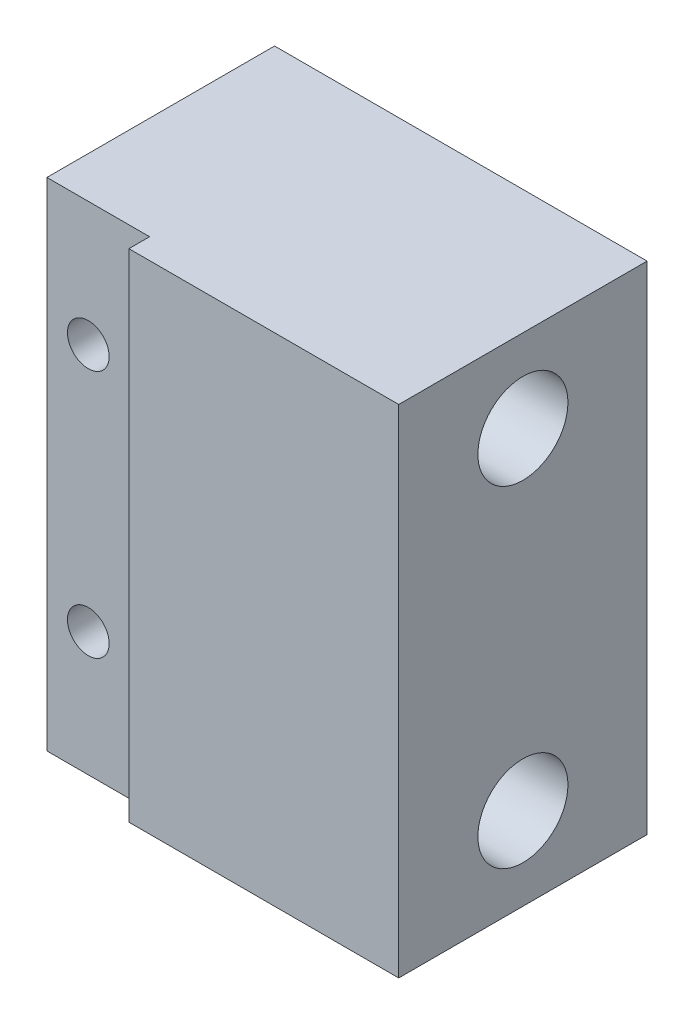
SolidWorks part; units mm, degrees
material "Delrin 2700 NC010, Low Viscosity Acetal Copolymer (SS)"
ref_plane "Front Plane" through (0, 0, 0) normal (0, 0, 1) x (1, 0, 0)
ref_plane "Top Plane" through (0, 0, 0) normal (0, 1, 0) x (1, 0, 0)
ref_plane "Right Plane" through (0, 0, 0) normal (1, 0, 0) x (0, 0, -1)
sketch "Sketch1" plane through (0, 0, 0) normal (1, 0, 0) x (0, 0, -1)
  line L1 (-4.7625, -9.525) -> (4.7625, -9.525)
  line L2 (-4.7625, -9.525) -> (-4.7625, 9.525)
  line L3 (-4.7625, 9.525) -> (4.7625, 9.525)
  line L4 (4.7625, -9.525) -> (4.7625, 9.525)
  line L5 (-4.7625, -9.525) -> (4.7625, 9.525) construction
  line L6 (-4.7625, 9.525) -> (4.7625, -9.525) construction
  point P0 (0, 0)
  dimension "D1" = 9.525
  dimension "D2" = 19.05
extrude "Boss-Extrude1" add sketch "Sketch1" against normal blind 14.2875
hole_wizard "#8-32 Tapped Hole1" positions "Sketch2" profile "Sketch3" tap size "#8-32" standard "ANSI Inch"
sketch "Sketch2" plane through (0, 0, 0) normal (1, 0, 0) x (0, 0, -1)
  point P0 (0, 6.35)
  point P2 (0, -6.35)
  point P13 (0, 0)
  dimension "D1" = 12.7
  dimension "D2" = 6.35
cosmetic thread "Hole Thread1" parameters "D1"=8.3312, "D2"=4.1656
cosmetic thread "Hole Thread2" parameters "D1"=8.3312, "D2"=4.1656
sketch "Sketch3" plane through (0, 6.35, 0) normal (0, 1, 0) x (0, 0, -1)
  line L0 (0, 0) -> (0, 12.4678)
  line L1 (0, 12.4678) -> (1.7272, 11.43)
  line L2 (1.7272, 11.43) -> (1.7272, 0)
  line L5 (1.7272, 0) -> (0, 0)
  line L10 (0, 12.4678) -> (-1.7272, 11.43) construction
  line L11 (0, -6.35) -> (0, 107.95) construction
  dimension "Tap Drill Dia." = 3.4544
  dimension "Tap Drill Depth" = 11.43
  dimension "Drill Angle" = 118
sketch "Sketch4" plane through (0, 9.525, 0) normal (0, 1, 0) x (1, 0, 0)
  line L0 (0, 4.7625) -> (0, -4.7625) construction
  line L1 (-14.2875, -4.7625) -> (-10.35, -4.7625)
  line L2 (-14.2875, -4.7625) -> (-14.2875, -3.9688)
  line L3 (-14.2875, -3.9688) -> (-10.35, -3.9688)
  line L4 (-10.35, -4.7625) -> (-10.35, -3.9688)
  dimension "D1" = 10.35
  dimension "D2" = 0.7937
extrude "Cut-Extrude1" cut sketch "Sketch4" against normal through all
hole_wizard "M2x0.4 Tapped Hole1" positions "Sketch5" profile "Sketch6" tap size "M2x0.4" standard "ANSI Metric" end condition through all
sketch "Sketch5" plane through (0, 0, 3.9687) normal (0, 0, 1) x (1, 0, 0)
  line L0 (-12.7, 4.765) -> (-12.7, -4.765) construction
  line L2 (0, 9.525) -> (0, -9.525) construction
  point P0 (-12.7, -4.765)
  point P2 (-12.7, 4.765)
  point P10 (-12.7, 0)
  dimension "D1" = 9.53
  dimension "D2" = 12.7
sketch "Sketch6" plane through (-12.7, -4.765, 3.9687) normal (1, 0, 0) x (0, -1, 0)
  line L0 (0, 0) -> (0, 8.7312)
  line L1 (0, 8.7312) -> (0.8, 8.7312)
  line L2 (0.8, 8.7312) -> (0.8, 0)
  line L5 (0.8, 0) -> (0, 0)
  line L11 (0, -6.35) -> (0, 107.95) construction
  dimension "Thru Tap Drill Dia." = 1.6
  dimension "Thru Tap Drill Depth" = 8.7312
cosmetic thread "Hole Thread3" parameters "D2"=2
cosmetic thread "Hole Thread4" parameters "D2"=2
equation "\"D2@Sketch2\"=\"D1@Sketch2\"/2"
equation "\"D1@Sketch4\"=.250+.250-2.35mm"
equation "\"D1@Sketch5\"=9.53mm"
equation "\"D1@Boss-Extrude1\"=0.625in-.0625"
